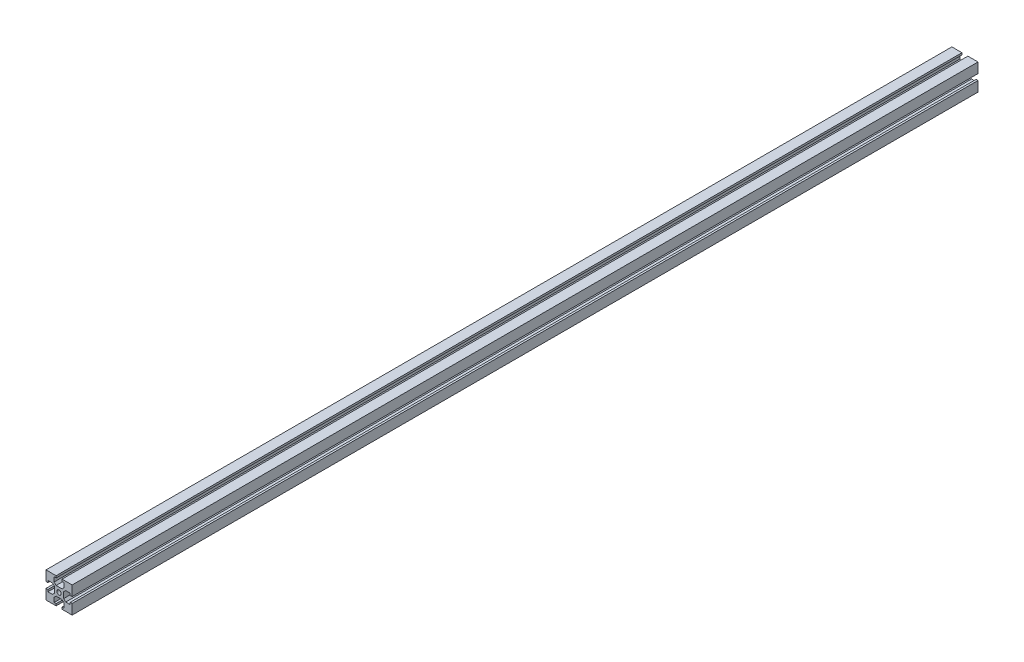
SolidWorks part; units mm, degrees
ref_plane "正面" through (0, 0, 0) normal (0, 0, 1) x (1, 0, 0)
ref_plane "平面" through (0, 0, 0) normal (0, 1, 0) x (1, 0, 0)
ref_plane "右側面" through (0, 0, 0) normal (1, 0, 0) x (0, 0, -1)
sketch "ｽｹｯﾁ2" plane through (0, 0, 0) normal (0, 0, 1) x (1, 0, 0)
  line L0 (0, 0) -> (0, 7.5) construction
  line L1 (-7.5, -7.5) -> (7.5, -7.5) construction
  line L2 (-7.5, -7.5) -> (-7.5, 7.5) construction
  line L3 (-7.5, 7.5) -> (7.5, 7.5) construction
  line L4 (7.5, -7.5) -> (7.5, 7.5) construction
  line L5 (-7.5, -7.5) -> (7.5, 7.5) construction
  line L6 (-7.5, 7.5) -> (7.5, -7.5) construction
  line L8 (1.7, 2.65) -> (-1.7, 2.65)
  line L9 (-2.85, 3.8) -> (2.85, 3.8) construction
  line L10 (-2.85, 6.4) -> (-2.85, 3.8)
  line L11 (2.85, 6.4) -> (2.85, 3.8)
  line L12 (-2.85, 3.8) -> (-1.7, 2.65)
  line L13 (1.7, 2.65) -> (2.85, 3.8)
  line L14 (-2.85, 6.4) -> (-1.7, 6.4)
  line L15 (-1.7, 6.4) -> (-1.7, 7.5)
  line L16 (-1.7, 7.5) -> (-7.5, 7.5)
  line L17 (2.85, 6.4) -> (1.7, 6.4)
  line L18 (1.7, 6.4) -> (1.7, 7.5)
  line L19 (1.7, 7.5) -> (7.5, 7.5)
  line L20 (3.8, 2.85) -> (2.65, 1.7)
  line L21 (2.65, -1.7) -> (2.65, 1.7)
  line L22 (2.65, -1.7) -> (3.8, -2.85)
  line L23 (6.4, -2.85) -> (6.4, -1.7)
  line L24 (6.4, -2.85) -> (3.8, -2.85)
  line L25 (6.4, -1.7) -> (7.5, -1.7)
  line L26 (7.5, -1.7) -> (7.5, -7.5)
  line L27 (6.4, 1.7) -> (7.5, 1.7)
  line L28 (7.5, 1.7) -> (7.5, 7.5)
  line L29 (6.4, 2.85) -> (6.4, 1.7)
  line L30 (6.4, 2.85) -> (3.8, 2.85)
  line L31 (2.85, -3.8) -> (1.7, -2.65)
  line L32 (-1.7, -2.65) -> (1.7, -2.65)
  line L33 (-1.7, -2.65) -> (-2.85, -3.8)
  line L34 (-2.85, -6.4) -> (-1.7, -6.4)
  line L35 (-2.85, -6.4) -> (-2.85, -3.8)
  line L36 (-1.7, -6.4) -> (-1.7, -7.5)
  line L37 (-1.7, -7.5) -> (-7.5, -7.5)
  line L38 (1.7, -6.4) -> (1.7, -7.5)
  line L39 (1.7, -7.5) -> (7.5, -7.5)
  line L40 (2.85, -6.4) -> (1.7, -6.4)
  line L41 (2.85, -6.4) -> (2.85, -3.8)
  line L42 (-3.8, -2.85) -> (-2.65, -1.7)
  line L43 (-2.65, 1.7) -> (-2.65, -1.7)
  line L44 (-2.65, 1.7) -> (-3.8, 2.85)
  line L45 (-6.4, 2.85) -> (-6.4, 1.7)
  line L46 (-6.4, 2.85) -> (-3.8, 2.85)
  line L47 (-6.4, 1.7) -> (-7.5, 1.7)
  line L48 (-7.5, 1.7) -> (-7.5, 7.5)
  line L49 (-6.4, -1.7) -> (-7.5, -1.7)
  line L50 (-7.5, -1.7) -> (-7.5, -7.5)
  line L51 (-6.4, -2.85) -> (-6.4, -1.7)
  line L52 (-6.4, -2.85) -> (-3.8, -2.85)
  circle A0 centre (0, 0) radius 1.25
  point P0 (0, 0)
  point P11 (0, 7.5)
  point P14 (0, 2.65)
  point P17 (0, 3.8)
  dimension "D8" = 2.5
  dimension "D1" = 15
  dimension "D2" = 3.4
  dimension "D3" = 1.1
  dimension "D4" = 2.6
  dimension "D5" = 5.7
  dimension "D6" = 3.4
  dimension "D7" = 4
extrude "ﾎﾞｽ - 押し出し1" add sketch "ｽｹｯﾁ2" along normal blind 520
